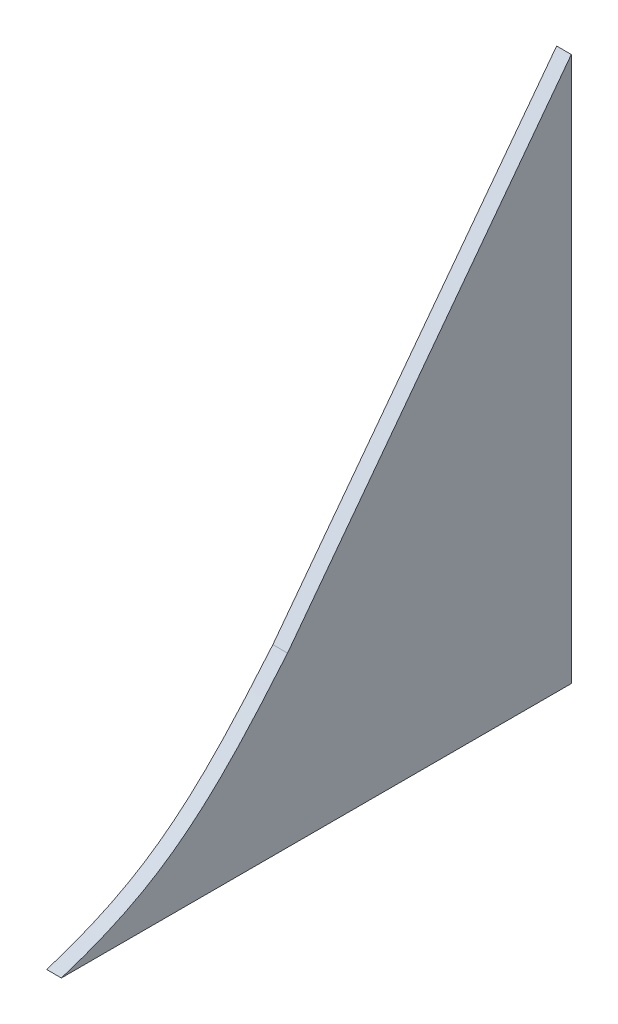
SolidWorks part; units mm, degrees
material "ASTM A36 Steel"
ref_plane "Front Plane" through (0, 0, 0) normal (0, 0, 1) x (1, 0, 0)
ref_plane "Top Plane" through (0, 0, 0) normal (0, 1, 0) x (1, 0, 0)
ref_plane "Right Plane" through (0, 0, 0) normal (1, 0, 0) x (0, 0, -1)
sketch "Sketch1" plane through (0, 0, 0) normal (1, 0, 0) x (0, 0, -1)
  line L0 (-114.3, 99.06) -> (-114.3, 0)
  line L1 (-114.3, 0) -> (-207.01, 0)
  line L2 (-114.3, 99.06) -> (-165.8906, 30.597)
  spline S0 degree 3 poles (-165.8906, 30.597) (-180.0952, 13.6197) (-188.627, 5.8018) (-207.01, 0) knots 0 0 0 0 1 1 1 1
  dimension "D5" = 85.725
  dimension "D1" = 99.06
  dimension "D2" = 92.71
  dimension "D3" = 114.3
  dimension "D4" = 37
extrude "Boss-Extrude1" add sketch "Sketch1" along normal blind 2.667
